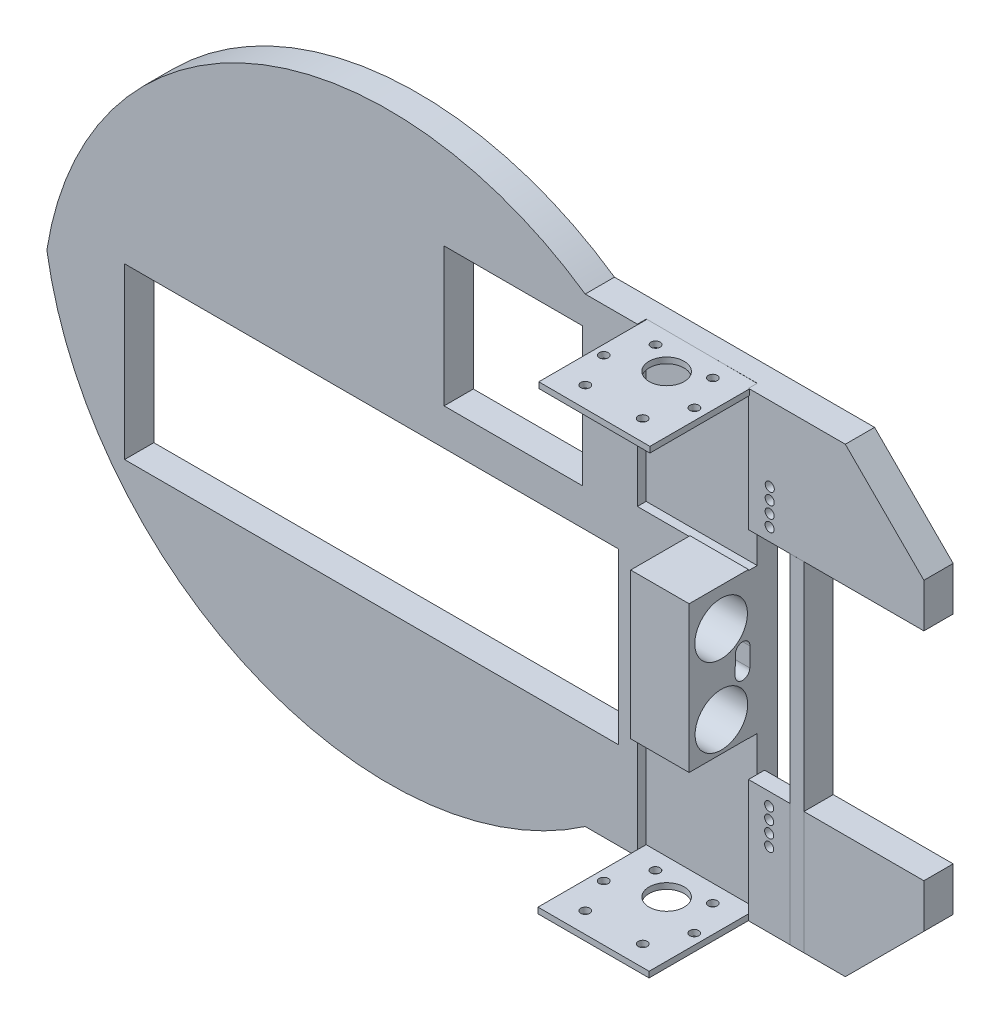
SolidWorks part; units mm, degrees
ref_plane "Front Plane" through (0, 0, 0) normal (0, 0, 1) x (1, 0, 0)
ref_plane "Top Plane" through (0, 0, 0) normal (0, 1, 0) x (1, 0, 0)
ref_plane "Right Plane" through (0, 0, 0) normal (1, 0, 0) x (0, 0, -1)
sketch "Sketch1" plane through (0, 0, 0) normal (0, 0, 1) x (1, 0, 0)
  line L1 (0, 0) -> (0, -37)
  line L2 (0, 37) -> (60, 37)
  line L3 (0, -37) -> (60, -37)
  line L4 (60, 37) -> (60, 52)
  line L5 (60, -37) -> (60, -52)
  line L6 (60, 52) -> (33.1299, 78.8701)
  line L7 (33.1299, 78.8701) -> (-55.8501, 78.8701)
  line L8 (60, -52) -> (33.1299, -78.8701)
  line L9 (33.1299, -78.8701) -> (-55.8501, -78.8701)
  line L10 (-55.8501, 78.8701) -> (-55.8501, 156.9436) construction
  line L11 (-55.8501, 156.9436) -> (-55.8501, -275.005) construction
  line L22 (0, 37) -> (0, 0)
  line L24 (-123.0632, 99.8019) -> (-270.1361, 99.8019) construction
  line L25 (-123.0632, 18.6512) -> (-123.0632, 134.1641) construction
  line L26 (-123.0632, -18.5763) -> (-123.0632, -116.9478) construction
  line L27 (-123.0632, -99.7887) -> (-269.8976, -99.7887) construction
  arc A7 (-239.9999, -0.1587) -> (-55.8501, 78.8701) centre (-123.0632, -18.5763) cw
  arc A8 (-55.8501, -78.8701) -> (-239.9999, -0.1587) centre (-123.0632, 18.6512) cw
  dimension "D11" = 199.5908
  dimension "D12" = 240
  dimension "D10" = 157.7401
  dimension "D1" = 37
  dimension "D2" = 37
  dimension "D3" = 60
  dimension "D4" = 15
  dimension "D5" = 15
  dimension "D6" = 135
  dimension "D7" = 38
  dimension "D8" = 38
  dimension "D9" = 135
  dimension "D15" = 88.98
  dimension "D16" = 88.98
extrude "Boss-Extrude1" add sketch "Sketch1" along normal blind 10 and the other way blind 0.01
sketch "Sketch3" plane through (0, 0, 10) normal (0, 0, 1) x (1, 0, 0)
  line L0 (33.1299, 78.8701) -> (-55.8501, 78.8701) construction
  line L1 (-38, 78.8701) -> (0, 78.8701)
  line L2 (-38, 78.8701) -> (-38, 24.8701)
  line L3 (-38, 24.8701) -> (0, 24.8701)
  line L4 (0, 78.8701) -> (0, 24.8701)
  dimension "D1" = 54
extrude "Cut-Extrude1" cut sketch "Sketch3" against normal blind 3 contours L2 L1 L4 L3
sketch "Sketch5" plane through (0, 0, 10) normal (0, 0, 1) x (1, 0, 0)
  line L0 (-55.8501, -78.8701) -> (33.1299, -78.8701) construction
  line L1 (-38, -24.8701) -> (0, -24.8701)
  line L2 (-38, -24.8701) -> (-38, -78.8701)
  line L3 (-38, -78.8701) -> (0, -78.8701)
  line L4 (0, -24.8701) -> (0, -78.8701)
  dimension "D1" = 54
extrude "Cut-Extrude3" cut sketch "Sketch5" against normal blind 3
sketch "Sketch7" plane through (0, 0, 10) normal (0, 0, 1) x (1, 0, 0)
  line L1 (-213.4131, 9.0562) -> (-44.4131, 9.0562)
  line L2 (-213.4131, 9.0562) -> (-213.4131, -48.9438)
  line L3 (-213.4131, -48.9438) -> (-44.4131, -48.9438)
  line L4 (-44.4131, 9.0562) -> (-44.4131, -48.9438)
  point P4 (0, 0)
  point P5 (0, 0)
  dimension "D1" = 58
  dimension "D2" = 169
extrude "Cut-Extrude4" cut sketch "Sketch7" against normal through all
sketch "Sketch8" plane through (0, 0, 10) normal (0, 0, 1) x (1, 0, 0)
  line L1 (-162.9927, 67.8133) -> (-84.7927, 67.8133)
  line L2 (-162.9927, 67.8133) -> (-162.9927, 10.3133)
  line L3 (-162.9927, 10.3133) -> (-84.7927, 10.3133)
  line L4 (-84.7927, 67.8133) -> (-84.7927, 10.3133)
  dimension "D1" = 78.2
  dimension "D2" = 57.5
extrude "Cut-Extrude5" [suppressed] cut sketch "Sketch8" against normal blind 3
sketch "Sketch9" plane through (0, 0, 10) normal (0, 0, 1) x (1, 0, 0)
  line L1 (-195, 36) -> (-176, 36)
  line L2 (-195, 36) -> (-195, 20)
  line L3 (-195, 20) -> (-176, 20)
  line L4 (-176, 36) -> (-176, 20)
  line L5 (-95.7317, 17.4542) -> (-82.493, 17.4542)
  line L6 (-95.7317, 17.4542) -> (-95.7317, 7.0108)
  line L7 (-95.7317, 7.0108) -> (-82.493, 7.0108)
  line L8 (-82.493, 17.4542) -> (-82.493, 7.0108)
  line L9 (-131.8867, -50.9252) -> (-116.9909, -50.9252)
  line L10 (-131.8867, -50.9252) -> (-131.8867, -65.1638)
  line L11 (-131.8867, -65.1638) -> (-116.9909, -65.1638)
  line L12 (-116.9909, -50.9252) -> (-116.9909, -65.1638)
extrude "Boss-Extrude2" [suppressed] add sketch "Sketch9" along normal blind 20.3
sketch "Sketch15" plane through (0, 0, 10) normal (0, 0, 1) x (1, 0, 0)
  line L0 (0, -24.8701) -> (0, 24.8701) construction
  line L1 (-20, 25.2016) -> (0, 25.2016)
  line L2 (-20, 25.2016) -> (-20, -24.7984)
  line L3 (-20, -24.7984) -> (0, -24.7984)
  line L4 (0, 25.2016) -> (0, -24.7984)
  dimension "D1" = 50
  dimension "D2" = 20
extrude "Boss-Extrude3" add sketch "Sketch15" along normal blind 20.3
sketch "Sketch16" plane through (0, 0, 10) normal (0, 0, 1) x (1, 0, 0)
  line L1 (-232.4208, 4) -> (-224.8235, 4)
  line L2 (-232.4208, 4) -> (-232.4208, -4)
  line L3 (-232.4208, -4) -> (-224.8235, -4)
  line L4 (-224.8235, 4) -> (-224.8235, -4)
  line L9 (-134.6881, 94.0493) -> (-144.6881, 94.0493)
  line L10 (-134.6881, 94.0493) -> (-134.6881, 84.6493)
  line L11 (-134.6881, 84.6493) -> (-144.6881, 84.6493)
  line L12 (-144.6881, 94.0493) -> (-144.6881, 84.6493)
  line L13 (-61.6779, 70.3488) -> (-70.3779, 70.3488)
  line L14 (-61.6779, 70.3488) -> (-61.6779, 61.8488)
  line L15 (-61.6779, 61.8488) -> (-70.3779, 61.8488)
  line L16 (-70.3779, 70.3488) -> (-70.3779, 61.8488)
  line L17 (-65.9779, -61.6233) -> (-75.3779, -61.6233)
  line L18 (-65.9779, -61.6233) -> (-65.9779, -70.9233)
  line L19 (-65.9779, -70.9233) -> (-75.3779, -70.9233)
  line L20 (-75.3779, -61.6233) -> (-75.3779, -70.9233)
  line L21 (-134.6881, -83.6815) -> (-144.6881, -83.6815)
  line L22 (-134.6881, -83.6815) -> (-134.6881, -92.9815)
  line L23 (-134.6881, -92.9815) -> (-144.6881, -92.9815)
  line L24 (-144.6881, -83.6815) -> (-144.6881, -92.9815)
  point P4 (0, 0)
  point P5 (0, 0)
  point P6 (0, 0)
  point P7 (0, 0)
extrude "Boss-Extrude4" [suppressed] add sketch "Sketch16" along normal blind 30
sketch "Sketch17" plane through (0, 0, 0) normal (0, 0, 1) x (1, 0, 0)
  circle A1 centre (-228.4208, 0) radius 2.55
  circle A2 centre (-139.6881, 89.6493) radius 3.5
  circle A3 centre (-65.8779, 66.3488) radius 3.5
  circle A4 centre (-69.8779, -66.6233) radius 3.5
  circle A5 centre (-139.6881, -88.6815) radius 3.5
  point P0 (0, 0)
extrude "Cut-Extrude17" [suppressed] cut sketch "Sketch17" along normal through all
sketch "Sketch18" plane through (0, 0, 10) normal (0, 0, 1) x (1, 0, 0)
  line L1 (-104.1245, 69) -> (-56.7245, 69)
  line L2 (-104.1245, 69) -> (-104.1245, 21.6)
  line L3 (-104.1245, 21.6) -> (-56.7245, 21.6)
  line L4 (-56.7245, 69) -> (-56.7245, 21.6)
  point P4 (0, 0)
  dimension "D1" = 47.4
  dimension "43.4" = 47.4
extrude "Cut-Extrude18" cut sketch "Sketch18" against normal through all
sketch "Sketch20" plane through (0, 0, 0) normal (0, 0, 1) x (1, 0, 0)
  circle A0 centre (-185.9471, 27.1121) radius 5
  circle A1 centre (-124.7094, -57.6129) radius 5
  circle A2 centre (-88.8879, 12.7504) radius 4
extrude "Cut-Extrude20" [suppressed] cut sketch "Sketch20" along normal through all
sketch "Sketch21" plane through (0, 0, 0) normal (1, 0, 0) x (0, 0, -1)
  line L0 (-3.8276, 29.0855) -> (-3.8276, -37.1575) construction
  line L1 (-6.4886, 28.3852) -> (-6.4886, -37.2976) construction
  line L2 (-5.0881, 28.1051) -> (-5.0881, -37.5777) construction
  line L3 (-11.99, 2.3019) -> (-12.0559, -4.1532) construction
  line L4 (-9.4916, 2.2764) -> (-9.5574, -4.1787)
  line L5 (-14.4885, 2.3274) -> (-14.5544, -4.1277)
  circle A0 centre (-19.3619, 12.3718) radius 9
  circle A1 centre (-19.2654, -14.6282) radius 9
  arc A2 (-9.4916, 2.2764) -> (-14.4885, 2.3274) centre (-11.99, 2.3019) ccw
  arc A3 (-14.5544, -4.1277) -> (-9.5574, -4.1787) centre (-12.0559, -4.1532) ccw
  point P12 (-12.023, -0.9256)
  dimension "D1" = 18
  dimension "D2" = 18
  dimension "D3" = 27
extrude "Cut-Extrude21" cut sketch "Sketch21" against normal up to surface (20 mm away) up to face at (-20, 5.1353, 18.12)
sketch "Sketch22" plane through (0, 0, 7) normal (0, 0, 1) x (1, 0, 0)
  circle A0 centre (-88.1686, 58.9795) radius 1.55
  circle A1 centre (-48.7686, 58.9795) radius 1.55
  circle A2 centre (-48.7686, 19.5795) radius 1.55
  circle A3 centre (-88.1686, 19.5795) radius 1.55
  dimension "D1" = 2
  dimension "D2" = 2
extrude "Cut-Extrude23" [suppressed] cut sketch "Sketch22" against normal through all
sketch "Sketch25" plane through (0, 0, 10) normal (0, 0, 1) x (1, 0, 0)
  line L1 (-173.6964, 70.8495) -> (-165.5964, 70.8495)
  line L2 (-173.6964, 70.8495) -> (-173.6964, 11.3495)
  line L3 (-173.6964, 11.3495) -> (-165.5964, 11.3495)
  line L4 (-165.5964, 70.8495) -> (-165.5964, 11.3495)
  dimension "D1" = 8.1
  dimension "D2" = 59.5
extrude "Boss-Extrude5" [suppressed] add sketch "Sketch25" along normal blind 3.5
sketch "Sketch26" [suppressed] plane through (0, 11.3495, 0) normal (0, -1, 0) x (1, 0, 0)
  line L0 (-172.679, 10.0037) -> (-152.674, 9.9893) construction
  line L1 (-152.674, 9.9893) -> (-152.6595, 14.6073) construction
  line L2 (-165.5928, 10.0085) -> (-173.4128, 10.0085)
  line L3 (-173.4128, 10.0085) -> (-173.4128, 12.4083)
  line L4 (-173.4128, 12.4083) -> (-165.5928, 12.4083)
  line L5 (-165.5928, 12.4083) -> (-165.5928, 10.0083)
  line M7 (-165.5964, 10) -> (-165.5964, 13.5)
extrude "Cut-Extrude24" [suppressed] cut sketch "Sketch26" against normal up to surface (59.5 mm away) contours L4 L3 L2 M7
sketch "Sketch28" plane through (0, -78.8701, 0) normal (0, -1, 0) x (1, 0, 0)
  line L1 (14.2266, 10.0076) -> (18.9795, 10.0076)
  line L2 (14.2266, 10.0076) -> (14.2266, 0.0598)
  line L3 (14.2266, 0.0598) -> (18.9795, 0.0598)
  line L4 (18.9795, 10.0076) -> (18.9795, 0.0598)
extrude "Boss-Extrude6" add sketch "Sketch28" against normal up to surface (115.8701 mm away) up to face at (24, 37, 5.396)
sketch "Sketch30" plane through (0, 0, -0.01) normal (0, 0, -1) x (-1, 0, 0)
  line L0 (0.5881, -0.0011) -> (-26.6848, -0.0585) construction
  line L1 (0, -62) -> (-14.12, -62)
  line L2 (0, -62) -> (0, -37)
  line L3 (0, -37) -> (-14.12, -37)
  line L4 (-14.12, -62) -> (-14.12, -37)
  line L5 (-14.3807, 61.9354) -> (-14.2755, 36.9356)
  line L6 (-0.1557, 36.995) -> (-14.2755, 36.9356)
  line L7 (-0.2608, 61.9948) -> (-0.1557, 36.995)
  line L8 (-0.2608, 61.9948) -> (-14.3807, 61.9354)
  dimension "D1" = 25
  dimension "D2" = 14.12
extrude "Cut-Extrude25" cut sketch "Sketch30" against normal blind 4.5
sketch "Sketch33" plane through (0, 0, -0.01) normal (0, 0, -1) x (-1, 0, 0)
  line L0 (0, 0) -> (-115.8951, -0.2361) construction
  circle A0 centre (-7.06, -53.4) radius 1.55
  circle A1 centre (-7.06, -49.4) radius 1.55
  circle A2 centre (-7.06, -45.4) radius 1.55
  circle A3 centre (-7.06, -41.4) radius 1.55
  circle A4 centre (-7.2286, 41.3709) radius 1.55
  circle A5 centre (-7.2449, 45.3709) radius 1.55
  circle A6 centre (-7.2612, 49.3708) radius 1.55
  circle A7 centre (-7.2775, 53.3708) radius 1.55
  dimension "D1" = 4
extrude "Cut-Extrude26" cut sketch "Sketch33" against normal up to surface (10.01 mm away) up to face at (7.1133, -57.935, 10)
sketch "Sketch34" plane through (0, 0, 10) normal (0, 0, 1) x (1, 0, 0)
  line L0 (0, 0) -> (85.4359, -0.2266) construction
  line L1 (53.8089, -34.3247) -> (61.9289, -40.2214)
  line L2 (53.8089, -34.3247) -> (57.1772, -29.6864)
  line L3 (61.9289, -40.2214) -> (65.2973, -35.5831)
  line L4 (57.1772, -29.6864) -> (65.2973, -35.5831)
  line L5 (62.1414, 39.8924) -> (65.4851, 35.2362)
  line L6 (57.3338, 29.3826) -> (65.4851, 35.2362)
  line L7 (53.9902, 34.0388) -> (57.3338, 29.3826)
  line L8 (53.9902, 34.0388) -> (62.1414, 39.8924)
extrude "Cut-Extrude27" [suppressed] cut sketch "Sketch34" against normal through all
sketch "Sketch36" plane through (0, 0, 7) normal (0, 0, 1) x (1, 0, 0)
  line L0 (0, 0) -> (106.9048, -0.1896) construction
  line L1 (0.2795, 78.8146) -> (0.2724, 76.8146)
  line L2 (0, -78.8151) -> (-38, -78.8151)
  line L3 (0, -78.8151) -> (0, -76.8151)
  line L4 (0, -76.8151) -> (-38, -76.8151)
  line L5 (-38, -78.8151) -> (-38, -76.8151)
  line L6 (-37.7202, 78.9494) -> (-37.7273, 76.9494)
  line L7 (0.2724, 76.8146) -> (-37.7273, 76.9494)
  line L8 (0.2795, 78.8146) -> (-37.7202, 78.9494)
  dimension "D1" = 2
extrude "Boss-Extrude7" add sketch "Sketch36" along normal blind 37
sketch "Sketch39" plane through (0, -78.8151, 0) normal (0, -1, 0) x (1, 0, 0)
  line L1 (-46.4365, 25) -> (22.9075, 25) construction
  line L4 (31.9978, 332) -> (-461.8231, 332) construction
  circle A1 centre (-19, 19) radius 6
  circle A2 centre (-34.4996, 25.0106) radius 1.55
  circle A3 centre (-3.5639, 24.9888) radius 1.55
  circle A4 centre (-28.8192, 37.0106) radius 1.55
  circle A5 centre (-9.1774, 36.9888) radius 1.55
  circle A6 centre (-28.82, 13.0106) radius 1.55
  circle A7 centre (-9.2305, 12.9888) radius 1.55
  point P18 (6.9989, 178.85)
  dimension "D1" = 12
  dimension "D5" = 12
  dimension "D6" = 12
  dimension "D7" = 12
  dimension "D8" = 12
  dimension "D2" = 19
extrude "Cut-Extrude28" cut sketch "Sketch39" against normal up to surface (2 mm away) up to face at (-19, -76.8151, 20.3333)
sketch "Sketch42" plane through (0.2795, 78.8146, 0) normal (0.0035, 1, 0) x (1, -0.0035, 0)
  circle A7 centre (-19.2797, -19) radius 6
  circle A9 centre (-29.0701, -13) radius 1.55
  circle A10 centre (-3.7784, -25) radius 1.55
  circle A11 centre (-9.4641, -13) radius 1.55
  circle A12 centre (-34.7723, -25) radius 1.55
  circle A13 centre (-29.0965, -37) radius 1.55
  circle A14 centre (-9.4734, -37) radius 1.55
  dimension "D1" = 12
  dimension "D5" = 6
  dimension "D6" = 6
  dimension "D7" = 6
  dimension "D8" = 6
  dimension "D9" = 18
  dimension "D10" = 18
  dimension "D2" = 19
extrude "Cut-Extrude29" cut sketch "Sketch42" against normal up to surface (2 mm away) up to face at (-12.485, 76.8599, 20.3333)
